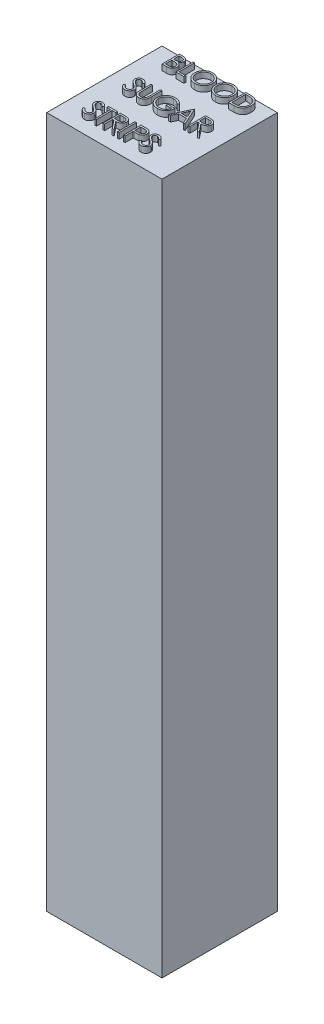
SolidWorks part; units mm, degrees
ref_plane "Front Plane" through (0, 0, 0) normal (0, 0, 1) x (1, 0, 0)
ref_plane "Top Plane" through (0, 0, 0) normal (0, 1, 0) x (1, 0, 0)
ref_plane "Right Plane" through (0, 0, 0) normal (1, 0, 0) x (0, 0, -1)
sketch "Sketch1" plane through (0, 0, 0) normal (0, 0, 1) x (1, 0, 0)
  line L1 (-5, 30) -> (5, 30)
  line L2 (-5, 30) -> (-5, -30)
  line L3 (-5, -30) -> (5, -30)
  line L4 (5, 30) -> (5, -30)
  line L5 (-5, 30) -> (5, -30) construction
  line L6 (-5, -30) -> (5, 30) construction
  point P0 (0, 0)
  dimension "D1" = 60
  dimension "D2" = 10
extrude "Boss-Extrude1" add sketch "Sketch1" along normal blind 10
sketch "Sketch2" plane through (0, 30, 0) normal (0, 1, 0) x (1, 0, 0)
  text T0 "BLOOD \r\nSUGAR \r\nSTRIPS" font "Century Gothic" height 1.5
extrude "Boss-Extrude2" add sketch "Sketch2" along normal blind 0.5
